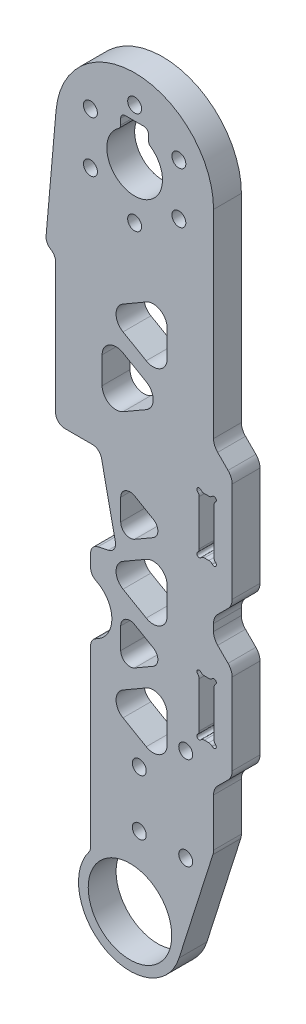
SolidWorks part; units mm, degrees
material "Thornel Mat VMA"
ref_plane "前视基准面" through (0, 0, 0) normal (0, 0, 1) x (1, 0, 0)
ref_plane "上视基准面" through (0, 0, 0) normal (0, 1, 0) x (1, 0, 0)
ref_plane "右视基准面" through (0, 0, 0) normal (1, 0, 0) x (0, 0, -1)
other "Configuration Table"
ref_plane "基准面1" through (0, 0, 0) normal (0, 0, -1) x (-1, 0, 0)
sketch "草图1" plane through (0, 0, 0) normal (0, 0, -1) x (-1, 0, 0)
  line L0 (-2.1075, 35.6677) -> (-1.1436, 35.6677)
  line L1 (-0.0256, 34.5497) -> (-0.0256, 24.7857)
  line L2 (-1.1436, 23.6677) -> (-2.1075, 23.6677)
  line L3 (-3.2256, 24.7857) -> (-3.2256, 34.5497)
  line L4 (10.8744, 95.4123) -> (10.8744, 96.6677)
  line L5 (11.8744, 97.6677) -> (15.8744, 97.6677)
  line L6 (16.8744, 96.6677) -> (16.8744, 95.4123)
  line L7 (11.3744, 65.1525) -> (16.3744, 62.2658)
  line L8 (16.3744, 57.0696) -> (11.3744, 54.1829)
  line L9 (6.8744, 56.7809) -> (6.8744, 62.5544)
  line L10 (6.8744, 8.7809) -> (6.8744, 14.5544)
  line L11 (11.3744, 17.1525) -> (16.3744, 14.2658)
  line L12 (16.3744, 9.0696) -> (11.3744, 6.1829)
  line L13 (13.8744, -4.3738) -> (9.8744, -2.0644)
  line L14 (9.8744, 1.3997) -> (13.8744, 3.7091)
  line L15 (16.8744, 1.9771) -> (16.8744, -2.6417)
  line L16 (6.8744, -15.2191) -> (6.8744, -9.4456)
  line L17 (11.3744, -6.8475) -> (16.3744, -9.7342)
  line L18 (16.3744, -14.9304) -> (11.3744, -17.8171)
  line L19 (9.8744, 25.3997) -> (13.8744, 27.7091)
  line L20 (16.8744, 25.9771) -> (16.8744, 21.3583)
  line L21 (13.8744, 19.6262) -> (9.8744, 21.9356)
  line L22 (20.8744, 50.5544) -> (20.8744, 44.7809)
  line L23 (16.3744, 42.1829) -> (11.3744, 45.0696)
  line L24 (11.3744, 50.2658) -> (16.3744, 53.1525)
  line L25 (-3.2256, -9.2143) -> (-3.2256, 0.5497)
  line L26 (-2.1075, 1.6677) -> (-1.1436, 1.6677)
  line L27 (-0.0256, 0.5497) -> (-0.0256, -9.2143)
  line L28 (-1.1436, -10.3323) -> (-2.1075, -10.3323)
  line L29 (32.9557, 66.6209) -> (30.8097, 91.1493)
  line L30 (-3.1256, 89.6677) -> (-3.1256, 46.9103)
  line L31 (-4.0042, 44.789) -> (-6.2469, 42.5464)
  line L32 (-7.1256, 40.4251) -> (-7.1256, 18.9103)
  line L33 (-6.2469, 16.789) -> (-4.0042, 14.5464)
  line L34 (-3.1256, 12.4251) -> (-3.1256, 10.9103)
  line L35 (-4.0042, 8.789) -> (-6.2469, 6.5464)
  line L36 (-7.1256, 4.4251) -> (-7.1256, -13.0897)
  line L37 (-6.2469, -15.211) -> (-4.0042, -17.4536)
  line L38 (-3.1256, -19.5749) -> (-3.1256, -29.8669)
  line L39 (-2.9845, -30.7759) -> (4.3019, -53.6937)
  line L40 (23.3496, -42.4759) -> (23.3496, -4.9027)
  line L41 (23.3496, 9.5472) -> (23.3496, 12.3199)
  line L42 (21.7655, 14.2762) -> (19.5635, 14.7443)
  line L43 (18.0231, 17.1164) -> (21.0129, 31.1826)
  line L44 (22.9692, 32.7667) -> (28.9071, 32.7667)
  line L45 (30.9071, 34.7667) -> (30.9071, 62.9159)
  arc A0 (-3.2256, 34.5497) -> (-3.5589, 35.295) centre (-4.2256, 34.5497) ccw
  arc A1 (-3.5589, 35.295) -> (-2.8529, 36.001) centre (-3.2256, 35.6677) cw
  arc A2 (-2.8529, 36.001) -> (-2.1075, 35.6677) centre (-2.1075, 36.6677) ccw
  arc A3 (-1.1436, 35.6677) -> (-0.3982, 36.001) centre (-1.1436, 36.6677) ccw
  arc A4 (-0.3982, 36.001) -> (0.3078, 35.295) centre (-0.0256, 35.6677) cw
  arc A5 (0.3078, 35.295) -> (-0.0256, 34.5497) centre (0.9744, 34.5497) ccw
  arc A6 (-0.0256, 24.7857) -> (0.3078, 24.0404) centre (0.9744, 24.7857) ccw
  arc A7 (0.3078, 24.0404) -> (-0.3982, 23.3344) centre (-0.0256, 23.6677) cw
  arc A8 (-0.3982, 23.3344) -> (-1.1436, 23.6677) centre (-1.1436, 22.6677) ccw
  arc A9 (-2.1075, 23.6677) -> (-2.8529, 23.3344) centre (-2.1075, 22.6677) ccw
  arc A10 (-2.8529, 23.3344) -> (-3.5589, 24.0404) centre (-3.2256, 23.6677) cw
  arc A11 (-3.5589, 24.0404) -> (-3.2256, 24.7857) centre (-4.2256, 24.7857) ccw
  circle A12 centre (13.8744, 89.6677) radius 11
  circle A13 centre (13.8744, 100.6677) radius 1.5
  circle A14 centre (4.3482, 95.1677) radius 1.5
  circle A15 centre (4.3482, 84.1677) radius 1.5
  circle A16 centre (13.8744, 78.6677) radius 1.5
  circle A17 centre (23.4007, 84.1677) radius 1.5
  arc A18 (16.8744, 95.4123) -> (17.303, 94.5916) centre (17.8744, 95.4123) ccw
  arc A19 (17.303, 94.5916) -> (10.4459, 94.5916) centre (13.8744, 89.6677) cw
  arc A20 (10.4459, 94.5916) -> (10.8744, 95.4123) centre (9.8744, 95.4123) ccw
  arc A21 (10.8744, 96.6677) -> (11.8744, 97.6677) centre (11.8744, 96.6677) cw
  arc A22 (15.8744, 97.6677) -> (16.8744, 96.6677) centre (15.8744, 96.6677) cw
  arc A23 (6.8744, 62.5544) -> (11.3744, 65.1525) centre (9.8744, 62.5544) cw
  arc A24 (16.3744, 62.2658) -> (16.3744, 57.0696) centre (14.8744, 59.6677) cw
  arc A25 (11.3744, 54.1829) -> (6.8744, 56.7809) centre (9.8744, 56.7809) cw
  arc A26 (11.3744, 6.1829) -> (6.8744, 8.7809) centre (9.8744, 8.7809) cw
  arc A27 (6.8744, 14.5544) -> (11.3744, 17.1525) centre (9.8744, 14.5544) cw
  arc A28 (16.3744, 14.2658) -> (16.3744, 9.0696) centre (14.8744, 11.6677) cw
  arc A29 (16.8744, -2.6417) -> (13.8744, -4.3738) centre (14.8744, -2.6417) cw
  arc A30 (9.8744, -2.0644) -> (9.8744, 1.3997) centre (10.8744, -0.3323) cw
  arc A31 (13.8744, 3.7091) -> (16.8744, 1.9771) centre (14.8744, 1.9771) cw
  circle A32 centre (12.8744, -22.3323) radius 1.5
  circle A33 centre (2.8744, -14.3323) radius 1.5
  circle A34 centre (12.8744, -34.3323) radius 1.5
  circle A35 centre (2.8744, -34.3323) radius 1.5
  circle A36 centre (14.8744, -50.3323) radius 9
  arc A37 (11.3744, -17.8171) -> (6.8744, -15.2191) centre (9.8744, -15.2191) cw
  arc A38 (6.8744, -9.4456) -> (11.3744, -6.8475) centre (9.8744, -9.4456) cw
  arc A39 (16.3744, -9.7342) -> (16.3744, -14.9304) centre (14.8744, -12.3323) cw
  arc A40 (9.8744, 21.9356) -> (9.8744, 25.3997) centre (10.8744, 23.6677) cw
  arc A41 (13.8744, 27.7091) -> (16.8744, 25.9771) centre (14.8744, 25.9771) cw
  arc A42 (16.8744, 21.3583) -> (13.8744, 19.6262) centre (14.8744, 21.3583) cw
  arc A43 (16.3744, 53.1525) -> (20.8744, 50.5544) centre (17.8744, 50.5544) cw
  arc A44 (20.8744, 44.7809) -> (16.3744, 42.1829) centre (17.8744, 44.7809) cw
  arc A45 (11.3744, 45.0696) -> (11.3744, 50.2658) centre (12.8744, 47.6677) cw
  arc A46 (-2.1075, -10.3323) -> (-2.8529, -10.6656) centre (-2.1075, -11.3323) ccw
  arc A47 (-2.8529, -10.6656) -> (-3.5589, -9.9596) centre (-3.2256, -10.3323) cw
  arc A48 (-3.5589, -9.9596) -> (-3.2256, -9.2143) centre (-4.2256, -9.2143) ccw
  arc A49 (-3.2256, 0.5497) -> (-3.5589, 1.295) centre (-4.2256, 0.5497) ccw
  arc A50 (-3.5589, 1.295) -> (-2.8529, 2.001) centre (-3.2256, 1.6677) cw
  arc A51 (-2.8529, 2.001) -> (-2.1075, 1.6677) centre (-2.1075, 2.6677) ccw
  arc A52 (-1.1436, 1.6677) -> (-0.3982, 2.001) centre (-1.1436, 2.6677) ccw
  arc A53 (-0.3982, 2.001) -> (0.3078, 1.295) centre (-0.0256, 1.6677) cw
  arc A54 (0.3078, 1.295) -> (-0.0256, 0.5497) centre (0.9744, 0.5497) ccw
  arc A55 (-0.0256, -9.2143) -> (0.3078, -9.9596) centre (0.9744, -9.2143) ccw
  arc A56 (0.3078, -9.9596) -> (-0.3982, -10.6656) centre (-0.0256, -10.3323) cw
  arc A57 (-0.3982, -10.6656) -> (-1.1436, -10.3323) centre (-1.1436, -11.3323) ccw
  arc A58 (30.9071, 62.9159) -> (31.7477, 64.5456) centre (32.9071, 62.9159) cw
  arc A59 (31.7477, 64.5456) -> (32.1487, 64.8358) centre (13.8744, 89.6677) ccw
  arc A60 (32.1487, 64.8358) -> (32.9557, 66.6209) centre (30.9633, 66.4466) ccw
  arc A61 (30.8097, 91.1493) -> (-3.1256, 89.6677) centre (13.8744, 89.6677) ccw
  arc A62 (-3.1256, 46.9103) -> (-4.0042, 44.789) centre (-6.1256, 46.9103) cw
  arc A63 (-6.2469, 42.5464) -> (-7.1256, 40.4251) centre (-4.1256, 40.4251) ccw
  arc A64 (-7.1256, 18.9103) -> (-6.2469, 16.789) centre (-4.1256, 18.9103) ccw
  arc A65 (-4.0042, 14.5464) -> (-3.1256, 12.4251) centre (-6.1256, 12.4251) cw
  arc A66 (-3.1256, 10.9103) -> (-4.0042, 8.789) centre (-6.1256, 10.9103) cw
  arc A67 (-6.2469, 6.5464) -> (-7.1256, 4.4251) centre (-4.1256, 4.4251) ccw
  arc A68 (-7.1256, -13.0897) -> (-6.2469, -15.211) centre (-4.1256, -13.0897) ccw
  arc A69 (-4.0042, -17.4536) -> (-3.1256, -19.5749) centre (-6.1256, -19.5749) cw
  arc A70 (-3.1256, -29.8669) -> (-2.9845, -30.7759) centre (-0.1256, -29.8669) ccw
  arc A71 (4.3019, -53.6937) -> (23.7496, -43.6759) centre (14.8744, -50.3323) ccw
  arc A72 (23.7496, -43.6759) -> (23.3496, -42.4759) centre (25.3496, -42.4759) cw
  arc A73 (23.3496, -4.9027) -> (22.2084, -3.0965) centre (21.3496, -4.9027) ccw
  arc A74 (22.2084, -3.0965) -> (22.2084, 7.7409) centre (24.7848, 2.3222) cw
  arc A75 (22.2084, 7.7409) -> (23.3496, 9.5472) centre (21.3496, 9.5472) ccw
  arc A76 (23.3496, 12.3199) -> (21.7655, 14.2762) centre (21.3496, 12.3199) ccw
  arc A77 (19.5635, 14.7443) -> (18.0231, 17.1164) centre (19.9794, 16.7006) cw
  arc A78 (21.0129, 31.1826) -> (22.9692, 32.7667) centre (22.9692, 30.7667) cw
  arc A79 (28.9071, 32.7667) -> (30.9071, 34.7667) centre (28.9071, 34.7667) ccw
  circle A81 centre (23.4007, 95.1677) radius 1.5
  point P207 (13.8744, 89.6677)
  dimension "D2" = 17
  dimension "D4" = 6
  dimension "D1" = 22
  dimension "D5" = 3
  dimension "D3" = 140
extrude "凸台-拉伸1" add sketch "草图1" against normal blind 6 contours A81 A12 A13 A14 A15 A16 A17 L5 A22 L6 A18 A19 A20 L4 A21 | L44 A79 L45 A58 A59 A60 L29 A61 L30 A62 L31 A63 L32 A64 L33 A65 L34 A66 L35 A67 L36 A68 L37 A69 L38 A70 L39 A71 A72 L40 A73 A74 A75 L41 A76 L42 A77 L43 A78 A81 A12 A17 A16 A15 A14 A13
